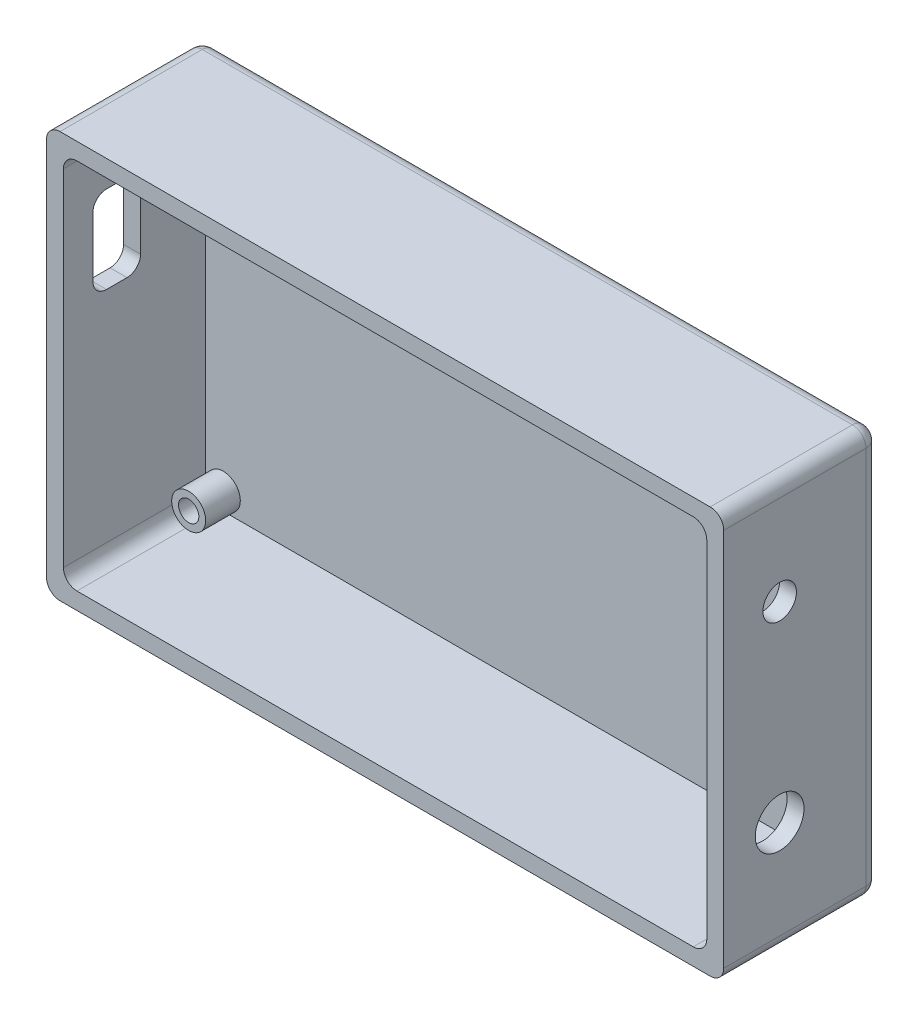
SolidWorks part; units mm, degrees
ref_plane "Front Plane" through (0, 0, 0) normal (0, 0, 1) x (1, 0, 0)
ref_plane "Top Plane" through (0, 0, 0) normal (0, 1, 0) x (1, 0, 0)
ref_plane "Right Plane" through (0, 0, 0) normal (1, 0, 0) x (0, 0, -1)
sketch "Sketch1" plane through (0, 0, 0) normal (0, 0, 1) x (1, 0, 0)
  line L1 (-50, -30) -> (50, -30)
  line L2 (-50, -30) -> (-50, 30)
  line L3 (-50, 30) -> (50, 30)
  line L4 (50, -30) -> (50, 30)
  line L5 (-50, -30) -> (50, 30) construction
  line L6 (-50, 30) -> (50, -30) construction
  point P0 (0, 0)
  dimension "D1" = 100
  dimension "D2" = 60
extrude "Boss-Extrude1" add sketch "Sketch1" along normal blind 23
sketch "Sketch2" plane through (0, 0, 23) normal (0, 0, 1) x (1, 0, 0)
  line L14 (-47.5, 27.5) -> (-47.5, -27.5)
  line L15 (-47.5, -27.5) -> (47.5, -27.5)
  line L16 (47.5, -27.5) -> (47.5, 27.5)
  line L17 (47.5, 27.5) -> (-47.5, 27.5)
  line L18 (-47.5, 27.5) -> (-47.5, -27.5)
  line L19 (-47.5, -27.5) -> (47.5, -27.5)
  line L20 (47.5, -27.5) -> (47.5, 27.5)
  line L21 (47.5, 27.5) -> (-47.5, 27.5)
  dimension "D1" = 2.5
extrude "Cut-Extrude1" cut sketch "Sketch2" against normal blind 21
sketch "Sketch3" plane through (0, 0, 2) normal (0, 0, 1) x (1, 0, 0)
  line L1 (50, 30) -> (-50, 30) construction
  line L2 (-50, 30) -> (-50, -30) construction
  line L7 (-47.5, 27.5) -> (-47.5, -27.5) construction
  circle A0 centre (-44.89, 24.89) radius 2.51
  circle A1 centre (-44.89, 24.89) radius 1.5
  point P4 (-44.89, 22.38)
  point P5 (-42.38, 24.89)
  point P8 (-44.89, 27.4344)
  point P11 (-47.4, 24.89)
  dimension "D1" = 7.62
  dimension "D3" = 3
  dimension "D2" = 7.62
  dimension "D4" = 0.1
extrude "Boss-Extrude6" add sketch "Sketch3" along normal blind 5.112
mirror "Mirror1" about plane through (0, 0, 0) normal (0, 1, 0) of "Boss-Extrude6"
mirror "Mirror2" about plane through (0, 0, 0) normal (1, 0, 0) of "Mirror1", "Boss-Extrude6"
fillet "Fillet1" radius 2 12 edges at (0, 30, 0) (-50, 30, 11.5) (-50, 0, 0) (-50, -30, 11.5) (0, -30, 0) (50, 0, 0) (50, 30, 11.5) (50, -30, 11.5) (47.5, -27.5, 12.5) (47.5, 27.5, 12.5) (-47.5, 27.5, 12.5) (-47.5, -27.5, 12.5)
sketch "Sketch4" plane through (-50, 0, 0) normal (-1, 0, 0) x (0, 0, 1)
  line L1 (18.6397, 19.7233) -> (11.612, 19.7233)
  line L2 (18.6397, 19.7233) -> (18.6397, 6.8794)
  line L3 (18.6397, 6.8794) -> (11.612, 6.8794)
  line L4 (11.612, 19.7233) -> (11.612, 6.8794)
extrude "Cut-Extrude2" cut sketch "Sketch4" against normal up to next
fillet "Fillet2" radius 2 4 edges at (-48.75, 19.7233, 11.612) (-48.75, 6.8794, 11.612) (-48.75, 6.8794, 18.6397) (-48.75, 19.7233, 18.6397)
sketch "Sketch5" plane through (50, 0, 0) normal (1, 0, 0) x (0, 0, -1)
  line L0 (-2, -30) -> (-23, -30) construction
  line L2 (-23, -28) -> (-23, 28) construction
  line L3 (-23, 30) -> (-2, 30) construction
  circle A0 centre (-14.745, -13.49) radius 3.6
  circle A1 centre (-14.74, 14.76) radius 2.475
  dimension "D1" = 16.51
  dimension "D3" = 7.2
  dimension "D6" = 4.95
  dimension "D2" = 8.255
  dimension "D4" = 8.26
  dimension "D5" = 15.24
extrude "Cut-Extrude3" cut sketch "Sketch5" against normal up to next
